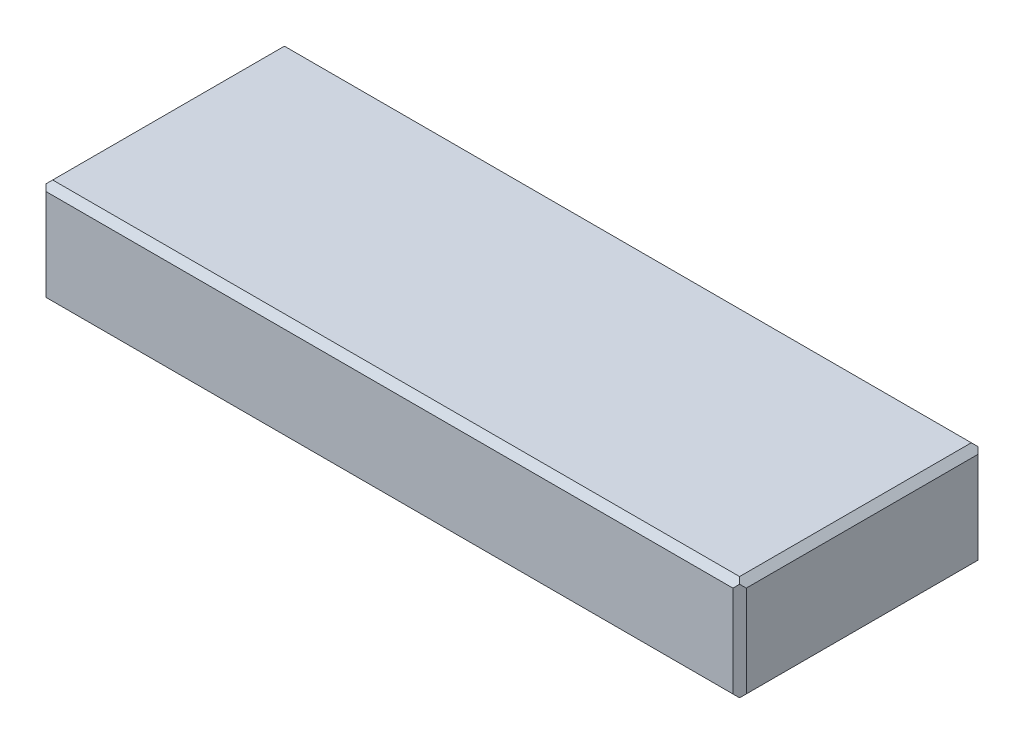
SolidWorks part; units mm, degrees
ref_plane "Plan de face" through (0, 0, 0) normal (0, 0, 1) x (1, 0, 0)
ref_plane "Plan de dessus" through (0, 0, 0) normal (0, 1, 0) x (1, 0, 0)
ref_plane "Plan de droite" through (0, 0, 0) normal (1, 0, 0) x (0, 0, -1)
sketch "Esquisse1" plane through (0, 0, 0) normal (0, 0, 1) x (1, 0, 0)
  line L1 (-49.1219, 29.1511) -> (160.8781, 29.1511)
  line L2 (-49.1219, 29.1511) -> (-49.1219, -2.3489)
  line L3 (-49.1219, -2.3489) -> (160.8781, -2.3489)
  line L4 (160.8781, 29.1511) -> (160.8781, -2.3489)
  dimension "D1" = 210
  dimension "D2" = 31.5
extrude "Extrusion1" add sketch "Esquisse1" along normal blind 73.5
chamfer "Chanfrein1" distance 2 angle 45 4 edges at (-49.1219, -2.3489, 36.75) (55.8781, -2.3489, 0) (55.8781, -2.3489, 73.5) (160.8781, -2.3489, 36.75)
chamfer "Chanfrein2" distance 2 angle 45 4 edges at (-49.1219, 29.1511, 36.75) (55.8781, 29.1511, 73.5) (160.8781, 29.1511, 36.75) (55.8781, 29.1511, 0)
chamfer "Chanfrein3" distance 2 angle 45 4 edges at (-49.1219, 13.4011, 73.5) (160.8781, 13.4011, 73.5) (160.8781, 13.4011, 0) (-49.1219, 13.4011, 0)
